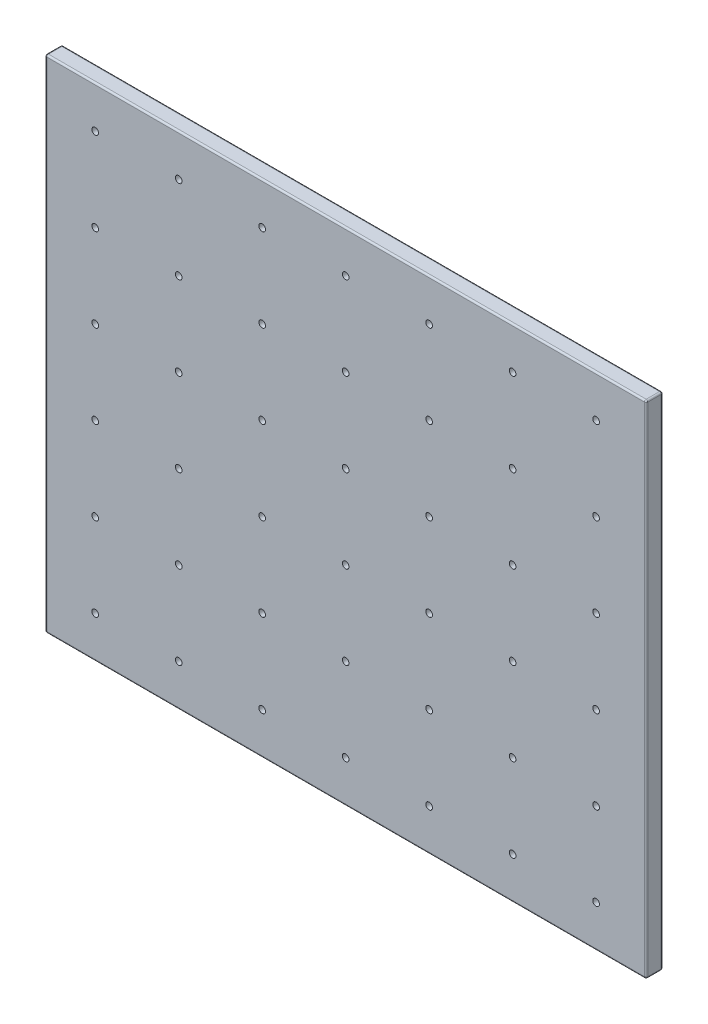
SolidWorks part; units mm, degrees
ref_plane "Front Plane" through (0, 0, 0) normal (0, 0, 1) x (1, 0, 0)
ref_plane "Top Plane" through (0, 0, 0) normal (0, 1, 0) x (1, 0, 0)
ref_plane "Right Plane" through (0, 0, 0) normal (1, 0, 0) x (0, 0, -1)
sketch "Sketch1" plane through (0, 0, 0) normal (0, 0, 1) x (1, 0, 0)
  line L0 (0, 0) -> (-179871.7364, 0) construction
  line L1 (0, 0) -> (0, 179871.7364) construction
  line L3 (360, -300) -> (-360, -300)
  line L4 (360, -300) -> (360, 300)
  line L5 (360, 300) -> (-360, 300)
  line L6 (-360, -300) -> (-360, 300)
  line L7 (360, -300) -> (-360, 300) construction
  line L8 (360, 300) -> (-360, -300) construction
  point P5 (0, 0)
  dimension "D1" = 720
  dimension "D2" = 600
extrude "Boss-Extrude1" add sketch "Sketch1" along normal blind 20
sketch "Sketch2" plane through (0, 0, 20) normal (0, 0, 1) x (1, 0, 0)
  line L0 (360, 300) -> (-360, 300) construction
  line L1 (-360, 300) -> (-360, -300) construction
  circle A0 centre (-300, 250) radius 4
  circle A1 centre (-200, 250) radius 4
  circle A2 centre (-100, 250) radius 4
  circle A3 centre (0, 250) radius 4
  circle A4 centre (100, 250) radius 4
  circle A5 centre (200, 250) radius 4
  circle A6 centre (300, 250) radius 4
  circle A7 centre (-200, 150) radius 4
  circle A8 centre (-100, 150) radius 4
  circle A9 centre (0, 150) radius 4
  circle A10 centre (100, 150) radius 4
  circle A11 centre (200, 150) radius 4
  circle A12 centre (300, 150) radius 4
  circle A13 centre (-200, 50) radius 4
  circle A14 centre (-100, 50) radius 4
  circle A15 centre (0, 50) radius 4
  circle A16 centre (100, 50) radius 4
  circle A17 centre (200, 50) radius 4
  circle A18 centre (300, 50) radius 4
  circle A19 centre (-200, -50) radius 4
  circle A20 centre (-100, -50) radius 4
  circle A21 centre (0, -50) radius 4
  circle A22 centre (100, -50) radius 4
  circle A23 centre (200, -50) radius 4
  circle A24 centre (300, -50) radius 4
  circle A25 centre (-200, -150) radius 4
  circle A26 centre (-100, -150) radius 4
  circle A27 centre (0, -150) radius 4
  circle A28 centre (100, -150) radius 4
  circle A29 centre (200, -150) radius 4
  circle A30 centre (300, -150) radius 4
  circle A31 centre (-300, 150) radius 4
  circle A32 centre (-300, 50) radius 4
  circle A33 centre (-300, -50) radius 4
  circle A34 centre (-300, -150) radius 4
  circle A35 centre (-300, 150) radius 4
  circle A36 centre (-300, 50) radius 4
  circle A37 centre (-300, -50) radius 4
  circle A38 centre (-300, -150) radius 4
  circle A39 centre (-300, -250) radius 4
  circle A40 centre (-200, 150) radius 4
  circle A41 centre (-200, 50) radius 4
  circle A42 centre (-200, -50) radius 4
  circle A43 centre (-200, -150) radius 4
  circle A44 centre (-200, -250) radius 4
  circle A45 centre (-100, 150) radius 4
  circle A46 centre (-100, 50) radius 4
  circle A47 centre (-100, -50) radius 4
  circle A48 centre (-100, -150) radius 4
  circle A49 centre (-100, -250) radius 4
  circle A50 centre (0, 150) radius 4
  circle A51 centre (0, 50) radius 4
  circle A52 centre (0, -50) radius 4
  circle A53 centre (0, -150) radius 4
  circle A54 centre (0, -250) radius 4
  circle A55 centre (100, 150) radius 4
  circle A56 centre (100, 50) radius 4
  circle A57 centre (100, -50) radius 4
  circle A58 centre (100, -150) radius 4
  circle A59 centre (100, -250) radius 4
  circle A60 centre (200, 150) radius 4
  circle A61 centre (200, 50) radius 4
  circle A62 centre (200, -50) radius 4
  circle A63 centre (200, -150) radius 4
  circle A64 centre (200, -250) radius 4
  circle A65 centre (300, 150) radius 4
  circle A66 centre (300, 50) radius 4
  circle A67 centre (300, -50) radius 4
  circle A68 centre (300, -150) radius 4
  circle A69 centre (300, -250) radius 4
  circle A70 centre (-200, 250) radius 4
  circle A71 centre (-100, 250) radius 4
  circle A72 centre (0, 250) radius 4
  circle A73 centre (100, 250) radius 4
  circle A74 centre (200, 250) radius 4
  circle A75 centre (300, 250) radius 4
  dimension "D1" = 8
  dimension "D2" = 50
  dimension "D3" = 60
  dimension "D4" = 7
  dimension "D5" = 5
  dimension "D6" = 6
  dimension "D7" = 7
fillet "Fillet1" radius 2 12 edges at (-360, 300, 10) (0, 300, 0) (0, 300, 20) (360, 300, 10) (360, 0, 0) (360, 0, 20) (360, -300, 10) (-360, 0, 0) (0, -300, 0) (-360, 0, 20) (0, -300, 20) (-360, -300, 10)
extrude "Cut-Extrude2" cut sketch "Sketch2" along direction (0, 0, 1) on the side of the normal through all and the other way blind 419 contours A0 | A1 | A2 | A7 | A13 | A19 | A25 | A34 | A39 | A44 | A33 | A32 | A8 | A3 | A4 | A5 | A11 | A10 | A9 | A6 | A12 | A18 | A24 | A23 | A17 | A16 | A22 | A14 | A20 | A21 | A15 | A26 | A27 | A28 | A29 | A30 | A49 | A54 | A59 | A64 | A69 | A31
